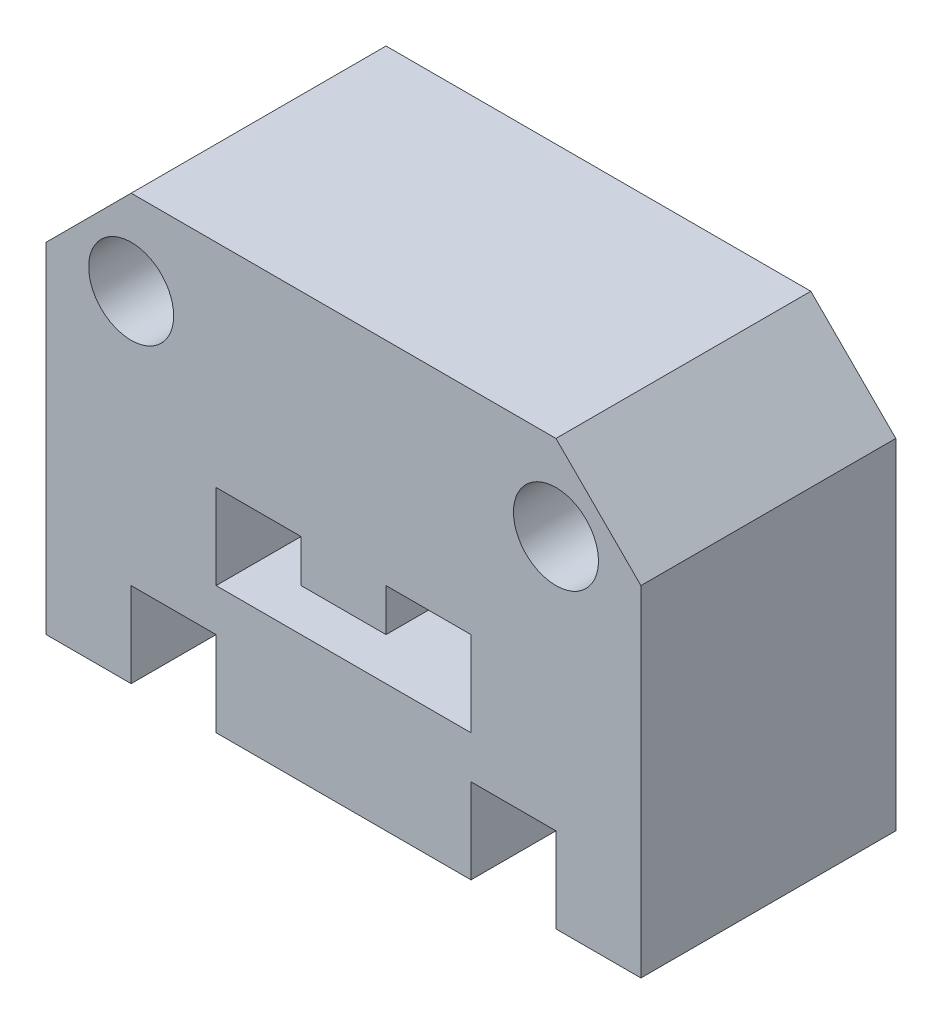
SolidWorks part; units mm, degrees
ref_plane "Front Plane" through (0, 0, 0) normal (0, 0, 1) x (1, 0, 0)
ref_plane "Top Plane" through (0, 0, 0) normal (0, 1, 0) x (1, 0, 0)
ref_plane "Right Plane" through (0, 0, 0) normal (1, 0, 0) x (0, 0, -1)
sketch "Sketch2" plane through (0, 0, 0) normal (0, 0, 1) x (1, 0, 0)
  line L0 (10, 10) -> (10, 50)
  line L3 (10, 10) -> (20, 10)
  line L4 (80, 50) -> (80, 10)
  line L7 (20, 60) -> (70, 60)
  line L8 (10, 50) -> (20, 60)
  line L9 (45, 76.4717) -> (45, -16.4717) construction
  line L10 (20, 10) -> (20, 20)
  line L11 (20, 20) -> (30, 20)
  line L12 (30, 20) -> (30, 10)
  line L13 (30, 10) -> (60, 10)
  line L14 (50, 30) -> (40, 30)
  line L15 (40, 30) -> (40, 35)
  line L16 (40, 35) -> (30, 35)
  line L17 (30, 35) -> (30, 25)
  line L18 (30, 25) -> (60, 25)
  line L19 (60, 35) -> (60, 25)
  line L20 (50, 35) -> (60, 35)
  line L21 (50, 30) -> (50, 35)
  line L22 (60, 20) -> (60, 10)
  line L23 (70, 20) -> (60, 20)
  line L24 (70, 10) -> (70, 20)
  line L25 (80, 50) -> (70, 60)
  line L26 (80, 10) -> (70, 10)
  circle A0 centre (20, 50) radius 5
  circle A1 centre (70, 50) radius 5
  point P3 (0, 0)
  point P4 (10, 60)
  point P7 (20, 50)
  point P11 (45, 30)
  point P13 (20, 15)
  point P27 (45, 25)
  point P30 (45, 30)
  point P36 (70, 50)
  point P37 (80, 60)
  dimension "D7" = 10
  dimension "D14" = 10
  dimension "D1" = 10
  dimension "D2" = 10
  dimension "D3" = 10
  dimension "D4" = 30
  dimension "D5" = 10
  dimension "D8" = 10
  dimension "D9" = 5
  dimension "D10" = 15
  dimension "D11" = 10
  dimension "D12" = 10
  dimension "D13" = 40
extrude "Boss-Extrude2" add sketch "Sketch2" along normal mid plane 30
